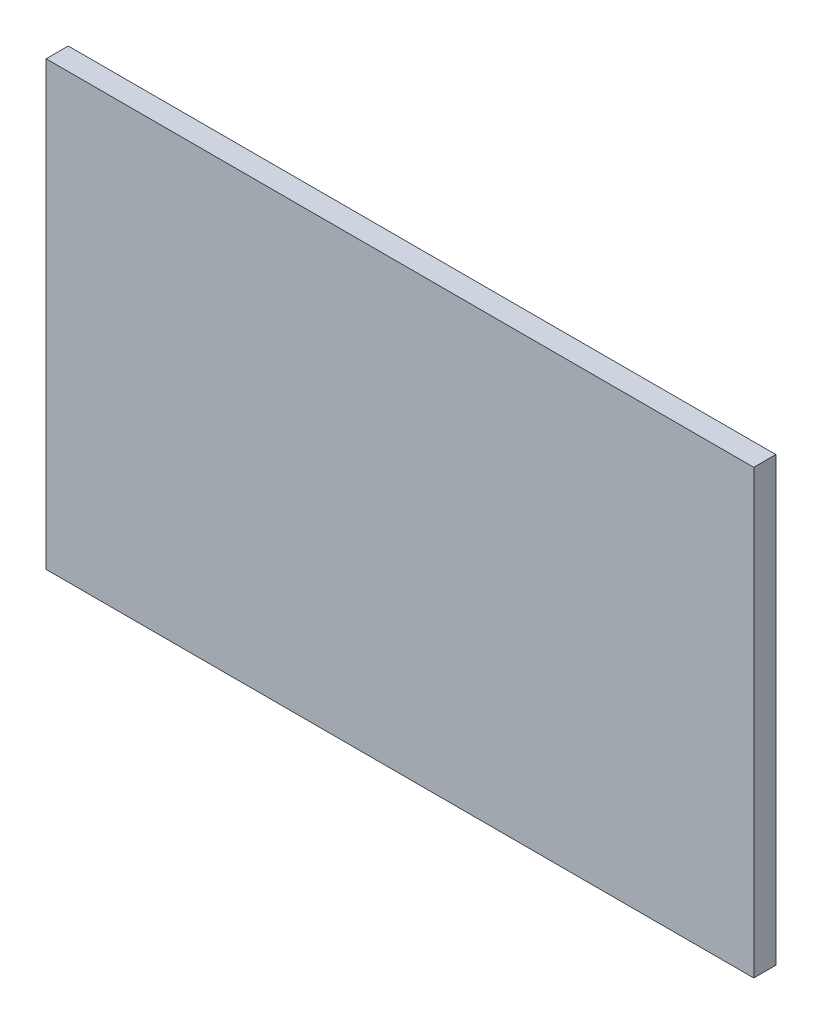
SolidWorks part; units mm, degrees
ref_plane "Front Plane" through (0, 0, 0) normal (0, 0, 1) x (1, 0, 0)
ref_plane "Top Plane" through (0, 0, 0) normal (0, 1, 0) x (1, 0, 0)
ref_plane "Right Plane" through (0, 0, 0) normal (1, 0, 0) x (0, 0, -1)
sketch "Sketch2" plane through (0, 0, 0) normal (0, 0, 1) x (1, 0, 0)
  line L1 (-400, 250) -> (400, 250)
  line L2 (-400, 250) -> (-400, -250)
  line L3 (-400, -250) -> (400, -250)
  line L4 (400, 250) -> (400, -250)
  line L5 (-400, 250) -> (400, -250) construction
  line L6 (-400, -250) -> (400, 250) construction
  point P0 (0, 0)
  dimension "D1" = 800
  dimension "D2" = 500
extrude "Boss-Extrude1" add sketch "Sketch2" along normal blind 25
